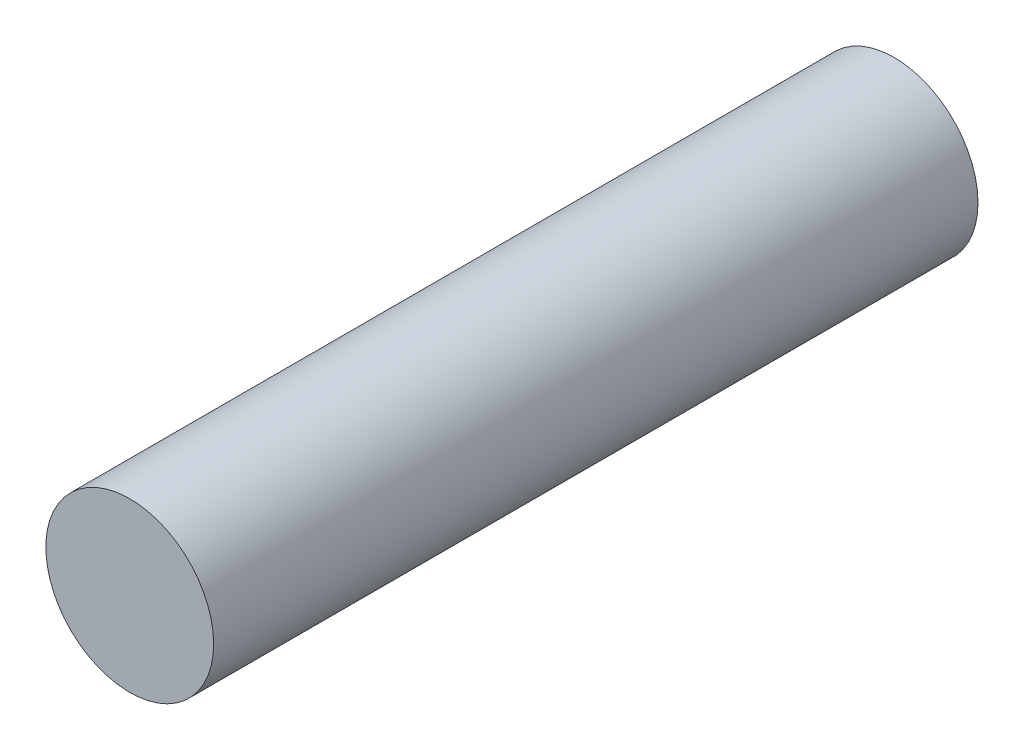
SolidWorks part; units mm, degrees
ref_plane "前视基准面" through (0, 0, 0) normal (0, 0, 1) x (1, 0, 0)
ref_plane "上视基准面" through (0, 0, 0) normal (0, 1, 0) x (1, 0, 0)
ref_plane "右视基准面" through (0, 0, 0) normal (1, 0, 0) x (0, 0, -1)
sketch "草图1" plane through (0, 0, 0) normal (0, 0, 1) x (1, 0, 0)
  circle A0 centre (0, 0) radius 4.5
  dimension "D1" = 9
extrude "凸台-拉伸1" add sketch "草图1" along normal blind 41
